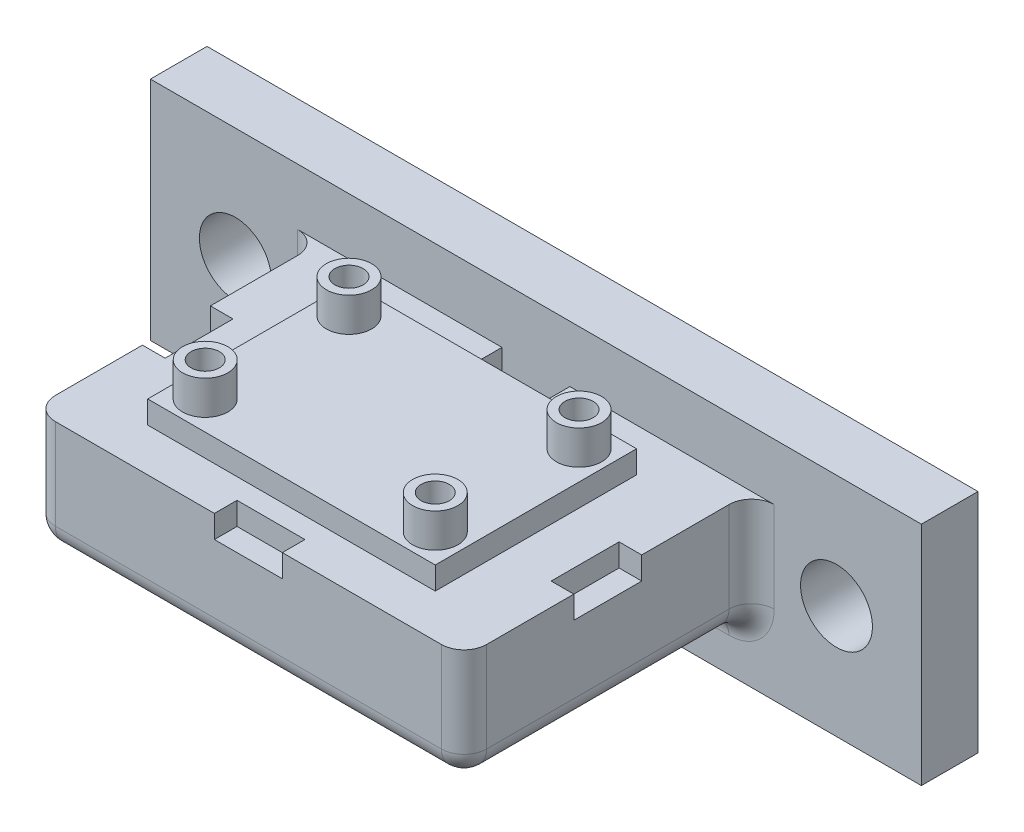
SolidWorks part; units mm, degrees
ref_plane "Front Plane" through (0, 0, 0) normal (0, 0, 1) x (1, 0, 0)
ref_plane "Top Plane" through (0, 0, 0) normal (0, 1, 0) x (1, 0, 0)
ref_plane "Right Plane" through (0, 0, 0) normal (1, 0, 0) x (0, 0, -1)
sketch "Sketch1" plane through (0, 0, 0) normal (0, 1, 0) x (1, 0, 0)
  circle A0 centre (-10.16, 6.35) radius 2
  circle A1 centre (10.16, 6.35) radius 2
  circle A2 centre (10.16, -6.35) radius 2
  circle A3 centre (-10.16, -6.35) radius 2
  dimension "D1" = 4
  dimension "D2" = 4
  dimension "D3" = 4
  dimension "D4" = 4
  dimension "D5" = 12.7
  dimension "D6" = 12.7
  dimension "D7" = 20.32
  dimension "D8" = 10.16
  dimension "D9" = 6.35
extrude "Boss-Extrude1" add sketch "Sketch1" along normal blind 5
sketch "Sketch3" plane through (0, 0, 0) normal (0, -1, 0) x (1, 0, 0)
  line L0 (-19.05, 12.7) -> (19.05, 12.7)
  line L1 (19.05, 12.7) -> (19.05, -12.7)
  line L2 (19.05, -12.7) -> (-19.05, -12.7)
  line L3 (-19.05, -12.7) -> (-19.05, 12.7)
  dimension "D1" = 19.05
  dimension "D2" = 19.05
  dimension "D3" = 12.7
  dimension "D4" = 12.7
extrude "Boss-Extrude2" add sketch "Sketch3" along normal blind 10
sketch "Sketch4" plane through (0, 0, 0) normal (0, 1, 0) x (1, 0, 0)
  line L1 (-12.7, 8.89) -> (12.7, 8.89)
  line L2 (-12.7, 8.89) -> (-12.7, -8.89)
  line L3 (-12.7, -8.89) -> (12.7, -8.89)
  line L4 (12.7, 8.89) -> (12.7, -8.89)
  point P0 (0, 0)
  dimension "D1" = 25.4
  dimension "D2" = 17.78
extrude "Boss-Extrude3" add sketch "Sketch4" along normal blind 2
sketch "Sketch2" plane through (0, 5, 0) normal (0, 1, 0) x (1, 0, 0)
  circle A0 centre (-10.16, 6.35) radius 1.25
  circle A1 centre (10.16, 6.35) radius 1.25
  circle A2 centre (10.16, -6.35) radius 1.25
  circle A3 centre (-10.16, -6.35) radius 1.25
  circle A4 centre (-10.16, -6.35) radius 2 construction
  circle A5 centre (-10.16, 6.35) radius 2 construction
  circle A6 centre (10.16, 6.35) radius 2 construction
  circle A7 centre (10.16, -6.35) radius 2 construction
  dimension "D1" = 20.32
  dimension "D2" = 12.7
  dimension "D3" = 6.35
  dimension "D4" = 10.16
extrude "Cut-Extrude1" cut sketch "Sketch2" against normal blind 10
sketch "Sketch6" plane through (0, 0, -12.7) normal (0, 0, -1) x (-1, 0, 0)
  line L2 (-2.9991, -2) -> (2.9991, -2)
  line L5 (-2.9991, -2) -> (-2.9991, 0)
  line L6 (19.05, 0) -> (-19.05, 0) construction
  line L7 (-2.9991, 0) -> (2.9991, 0)
  line L8 (-12.7, 0) -> (12.7, 0) construction
  line L9 (2.9991, 0) -> (2.9991, -2)
  point P6 (0, 0)
  point P10 (0, -2)
  dimension "D1" = 5.9982
  dimension "D2" = 2
extrude "Cut-Extrude3" cut sketch "Sketch6" against normal blind 2
mirror "Mirror1" about plane through (0, 0, 0) normal (0, 0, 1) of "Cut-Extrude3"
sketch "Sketch7" plane through (-19.05, 0, 0) normal (-1, 0, 0) x (0, 0, 1)
  line L2 (-2.997, -2) -> (3.003, -2)
  line L5 (-2.997, -2) -> (-2.997, 0)
  line L6 (12.7, 0) -> (-12.7, 0) construction
  line L7 (-2.997, 0) -> (3.003, 0)
  line L8 (-8.89, 0) -> (8.89, 0) construction
  line L9 (3.003, 0) -> (3.003, -2)
  point P6 (0, 0)
  point P10 (0.003, -2)
  dimension "D1" = 2
  dimension "D2" = 6
extrude "Cut-Extrude4" cut sketch "Sketch7" against normal blind 2
mirror "Mirror2" about plane through (0, 0, 0) normal (1, 0, 0) of "Cut-Extrude4"
sketch "Sketch8" plane through (0, 0, -12.7) normal (0, 0, -1) x (-1, 0, 0)
  line L7 (-34.05, -15) -> (34.05, -15)
  line L8 (-34.05, 5) -> (-34.05, -15)
  line L9 (-34.05, 5) -> (34.05, 5)
  line L10 (34.05, 5) -> (34.05, -15)
  line L11 (-34.05, -5) -> (34.05, -5) construction
  line L12 (19.05, -10) -> (-19.05, -10) construction
  line L14 (19.05, -10) -> (19.05, 0) construction
  line L15 (-19.05, -10) -> (-19.05, 0) construction
  dimension "D1" = 20
  dimension "D2" = 5
  dimension "D3" = 15
  dimension "D4" = 15
extrude "Boss-Extrude4" add sketch "Sketch8" along normal blind 5
sketch "Sketch9" plane through (0, 0, -12.7) normal (0, 0, 1) x (1, 0, 0)
  line L4 (-34.05, -15) -> (-34.05, 5) construction
  line L5 (-34.05, 5) -> (34.05, 5) construction
  line L6 (34.05, 5) -> (34.05, -15) construction
  circle A0 centre (-26.55, -5) radius 3.175
  circle A1 centre (26.55, -5) radius 3.175
  point P4 (0, 0)
  dimension "D1" = 6.35
  dimension "D2" = 7.5
  dimension "D6" = 6.35
  dimension "D3" = 10
  dimension "D4" = 7.5
  dimension "D5" = 10
extrude "Cut-Extrude5" cut sketch "Sketch9" against normal blind 5
fillet "Fillet1" radius 2 8 edges at (0, -10, -12.7) (19.05, -5, -12.7) (-19.05, -5, -12.7) (-19.05, -10, 0) (19.05, -10, 0) (0, -10, 12.7) (19.05, -5, 12.7) (-19.05, -5, 12.7)
